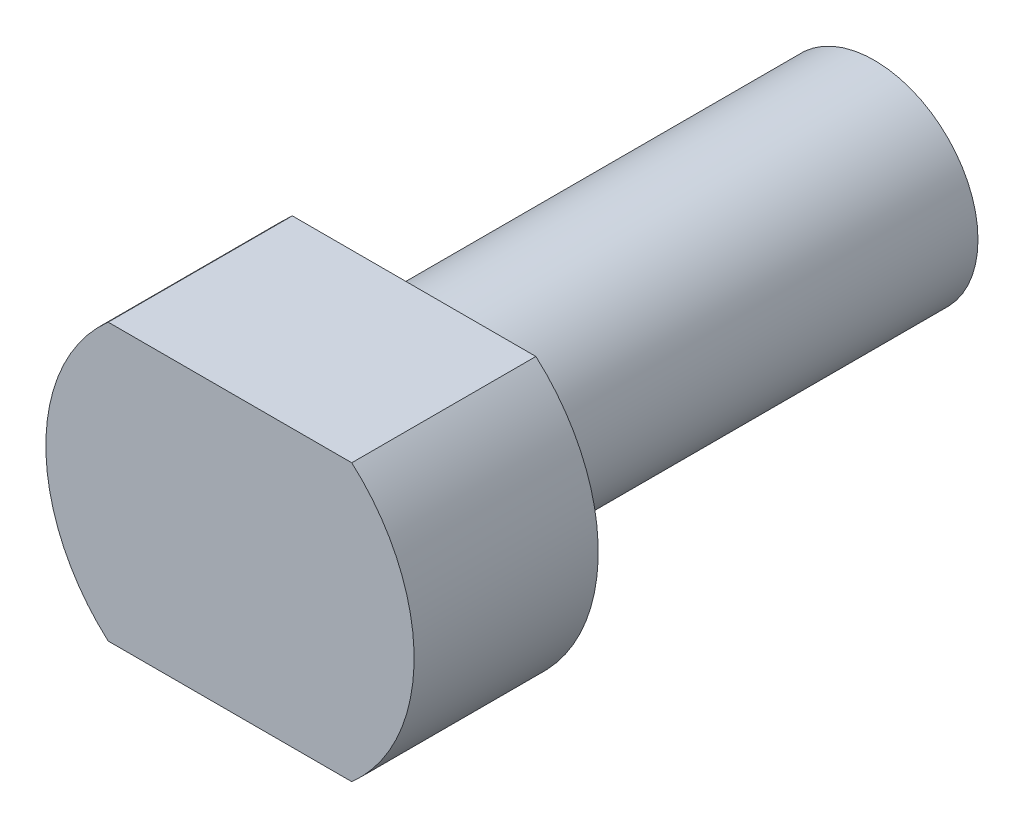
SolidWorks part; units mm, degrees
ref_plane "Front Plane" through (0, 0, 0) normal (0, 0, 1) x (1, 0, 0)
ref_plane "Top Plane" through (0, 0, 0) normal (0, 1, 0) x (1, 0, 0)
ref_plane "Right Plane" through (0, 0, 0) normal (1, 0, 0) x (0, 0, -1)
sketch "Sketch1" plane through (0, 0, 0) normal (0, 0, 1) x (1, 0, 0)
  circle A0 centre (0, 0) radius 2.25
  dimension "D1" = 4.5
extrude "Boss-Extrude1" add sketch "Sketch1" along normal blind 10 contours A0
sketch "Sketch2" plane through (0, 0, 10) normal (0, 0, 1) x (1, 0, 0)
  circle A0 centre (0, 0) radius 4
  dimension "D1" = 8
extrude "Boss-Extrude2" add sketch "Sketch2" along normal blind 4
sketch "Sketch3" plane through (0, 0, 14) normal (0, 0, 1) x (1, 0, 0)
  line L1 (-2.6458, 3) -> (2.6458, 3)
  line L3 (-2.6458, -3) -> (2.6458, -3)
  circle A0 centre (0, 0) radius 4 construction
  arc A1 (-2.6458, -3) -> (2.6458, -3) centre (0, 0) ccw
  arc A2 (2.6458, 3) -> (-2.6458, 3) centre (0, 0) ccw
  dimension "D1" = 6
extrude "Cut-Extrude1" cut sketch "Sketch3" against normal blind 4
